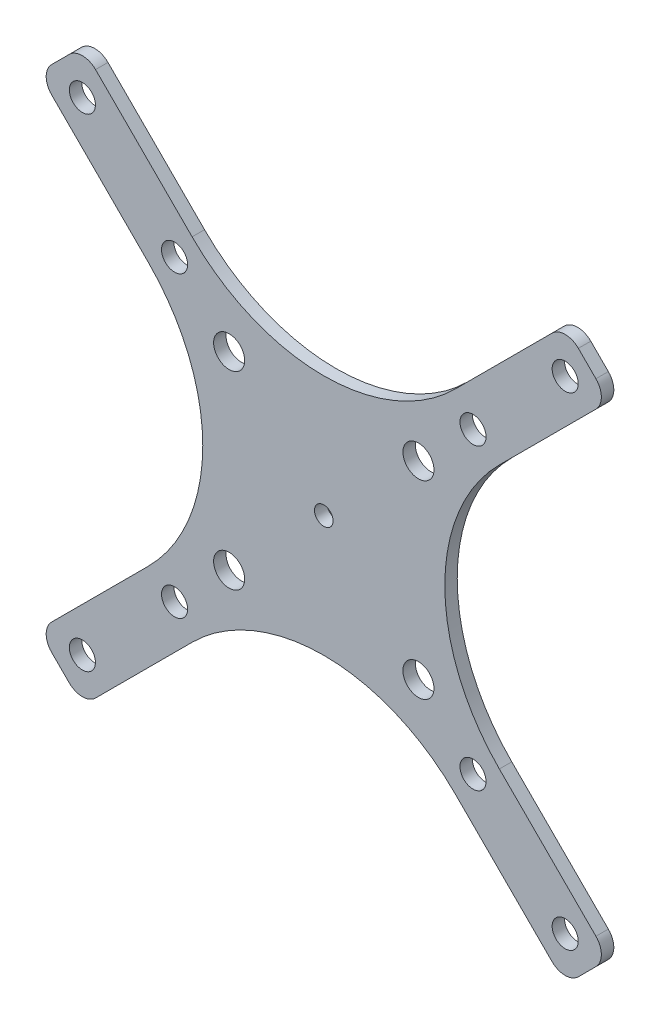
SolidWorks part; units mm, degrees
ref_plane "Alzado" through (0, 0, 0) normal (0, 0, 1) x (1, 0, 0)
ref_plane "Planta" through (0, 0, 0) normal (0, 1, 0) x (1, 0, 0)
ref_plane "Vista lateral" through (0, 0, 0) normal (1, 0, 0) x (0, 0, -1)
sketch "Croquis1" plane through (0, 0, 0) normal (0, 0, 1) x (1, 0, 0)
  line L0 (0, 0) -> (27.8544, 27.8544) construction
  line L1 (0, 0) -> (-42.4264, 42.4264) construction
  line L2 (-31.0962, 38.1673) -> (-21.2132, 28.2843)
  line L3 (15.25, -15.25) -> (-15.25, -15.25) construction
  line L4 (15.25, -15.25) -> (15.25, 15.25) construction
  line L5 (15.25, 15.25) -> (-15.25, 15.25) construction
  line L6 (-15.25, -15.25) -> (-15.25, 15.25) construction
  line L7 (15.25, -15.25) -> (-15.25, 15.25) construction
  line L8 (15.25, 15.25) -> (-15.25, -15.25) construction
  line L9 (21.2132, 28.2843) -> (31.0962, 38.1673)
  line L10 (-42.4264, 42.4264) -> (-38.8909, 45.9619)
  line L11 (-38.8909, 45.9619) -> (-31.0962, 38.1673)
  line L13 (-42.4264, 42.4264) -> (-45.9619, 38.8909)
  line L14 (-45.9619, 38.8909) -> (-38.1673, 31.0962)
  line L16 (38.8909, 45.9619) -> (31.0962, 38.1673)
  line L17 (42.4264, 42.4264) -> (38.8909, 45.9619)
  line L18 (42.4264, 42.4264) -> (45.9619, 38.8909)
  line L19 (-45.9619, -38.8909) -> (-38.1673, -31.0962)
  line L20 (0, 0) -> (-15.25, 0) construction
  line L21 (45.9619, 38.8909) -> (38.1673, 31.0962)
  line L22 (42.4264, -42.4264) -> (45.9619, -38.8909)
  line L23 (42.4264, -42.4264) -> (38.8909, -45.9619)
  line L24 (38.8909, -45.9619) -> (31.0962, -38.1673)
  line L27 (-38.8909, -45.9619) -> (-31.0962, -38.1673)
  line L28 (-42.4264, -42.4264) -> (-38.8909, -45.9619)
  line L29 (-42.4264, -42.4264) -> (-45.9619, -38.8909)
  line L30 (45.9619, -38.8909) -> (38.1673, -31.0962)
  line L31 (-31.0962, -38.1673) -> (-21.2132, -28.2843)
  line L32 (21.2132, -28.2843) -> (31.0962, -38.1673)
  line L33 (-38.1673, 31.0962) -> (-28.2843, 21.2132)
  line L34 (-28.2843, -21.2132) -> (-38.1673, -31.0962)
  line L35 (38.1673, 31.0962) -> (28.2843, 21.2132)
  line L36 (28.2843, -21.2132) -> (38.1673, -31.0962)
  circle A0 centre (-15.25, 15.25) radius 2.5
  circle A1 centre (-24.0416, 24.0416) radius 2.1
  circle A2 centre (-38.8909, 38.8909) radius 2.1
  circle A5 centre (38.8909, 38.8909) radius 2.1
  circle A6 centre (24.0416, 24.0416) radius 2.1
  circle A7 centre (15.25, 15.25) radius 2.5
  circle A8 centre (15.25, -15.25) radius 2.5
  circle A9 centre (24.0416, -24.0416) radius 2.1
  circle A10 centre (38.8909, -38.8909) radius 2.1
  circle A12 centre (-15.25, -15.25) radius 2.5
  circle A13 centre (-24.0416, -24.0416) radius 2.1
  circle A14 centre (-38.8909, -38.8909) radius 2.1
  circle A18 centre (0, 0) radius 1.5
  circle A20 centre (-16, -30) radius 3 construction
  circle A21 centre (-16, 30) radius 3 construction
  circle A24 centre (16, -30) radius 3 construction
  circle A25 centre (16, 30) radius 3 construction
  arc A91 (-21.2132, 28.2843) -> (21.2132, 28.2843) centre (0, 49.4975) ccw
  arc A92 (-21.2132, -28.2843) -> (21.2132, -28.2843) centre (0, -49.4975) cw
  arc A93 (-28.2843, 21.2132) -> (-28.2843, -21.2132) centre (-49.4975, 0) cw
  arc A94 (28.2843, 21.2132) -> (28.2843, -21.2132) centre (49.4975, 0) ccw
  point P35 (-34.9935, 42.0646)
  point P37 (44.1942, 40.6586)
  point P45 (44.1942, -40.6586)
  point P51 (-7.0711, 0)
  point P61 (-34.9935, -42.0646)
  dimension "D2" = 5
  dimension "D4" = 5
  dimension "D11" = 4.2
  dimension "D3" = 30
  dimension "D6" = 30
  dimension "D1" = 30.5
  dimension "D5" = 21
  dimension "D7" = 5
  dimension "D9" = 5
extrude "Saliente-Extruir1" add sketch "Croquis1" along normal blind 2
fillet "Redondeo3" radius 3 8 edges at (-45.9619, 38.8909, 1) (-38.8909, 45.9619, 1) (38.8909, 45.9619, 1) (45.9619, 38.8909, 1) (45.9619, -38.8909, 1) (38.8909, -45.9619, 1) (-45.9619, -38.8909, 1) (-38.8909, -45.9619, 1)
